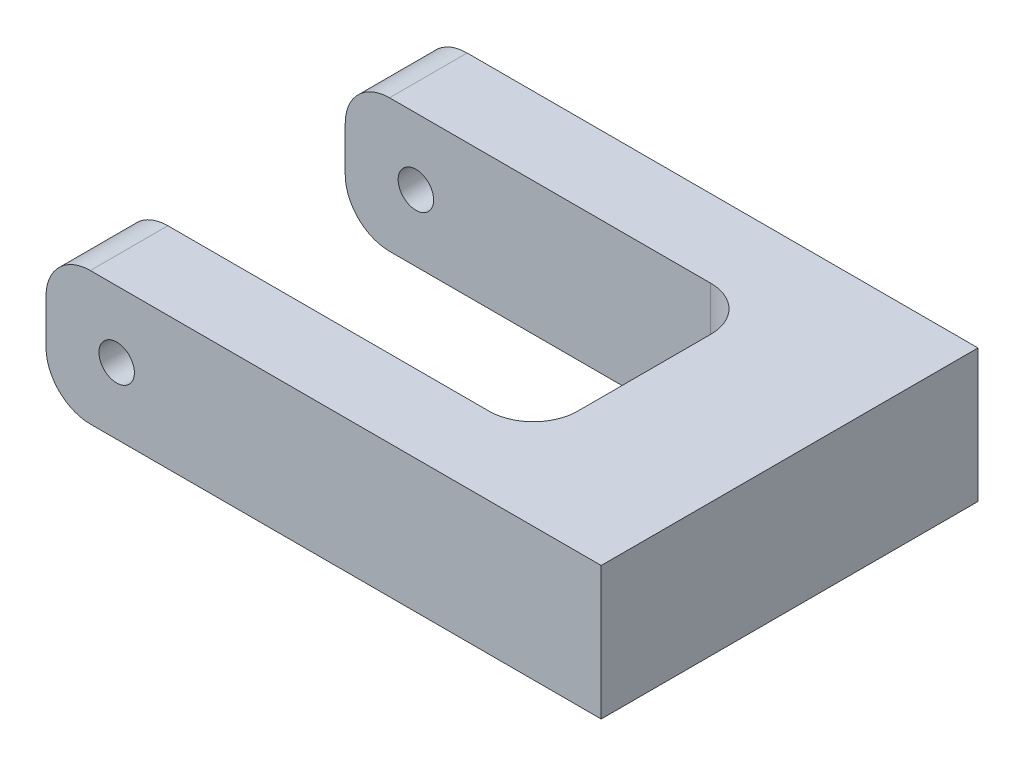
SolidWorks part; units mm, degrees
ref_plane "Спереди" through (0, 0, 0) normal (0, 0, 1) x (1, 0, 0)
ref_plane "Сверху" through (0, 0, 0) normal (0, 1, 0) x (1, 0, 0)
ref_plane "Справа" through (0, 0, 0) normal (1, 0, 0) x (0, 0, -1)
sketch "Эскиз1" plane through (0, 0, 0) normal (0, 0, 1) x (1, 0, 0)
  line L0 (-0.1149, -4.0419) -> (-0.1149, -14.0419)
  line L3 (9.8851, -24.0419) -> (125.1317, -24.0419)
  line L4 (9.8851, 5.9581) -> (125.1317, 5.9581)
  line L5 (125.1317, 5.9581) -> (125.1317, -24.0419)
  line L6 (15.824, -9.0419) -> (68.2142, -9.0419) construction
  arc A0 (-0.1149, -4.0419) -> (9.8851, 5.9581) centre (9.8851, -4.0419) cw
  arc A1 (-0.1149, -14.0419) -> (9.8851, -24.0419) centre (9.8851, -14.0419) ccw
  dimension "D1" = 10
  dimension "D2" = 15
extrude "Вытянуть1" add sketch "Эскиз1" against normal blind 85 from offset 7.5
sketch "Эскиз3" plane through (0, 0, 0) normal (0, 1, 0) x (1, 0, 0)
  line L0 (-2.2661, 60) -> (92.3282, 60)
  line L1 (92.3282, 60) -> (92.3282, 10)
  line L2 (92.3282, 10) -> (-2.2661, 10)
  line L4 (-2.2661, 10) -> (-2.2661, 60)
  line L8 (125.1317, 77.5) -> (9.8851, 77.5) construction
  line L9 (125.1317, -7.5) -> (9.8851, -7.5) construction
  dimension "D2" = 17.5
  dimension "D3" = 17.5
extrude "Вырез-Вытянуть1" cut sketch "Эскиз3" against normal mid plane 87
sketch "Эскиз4" plane through (0, 0, 0) normal (0, 0, 1) x (1, 0, 0)
  circle A0 centre (15.824, -9.0419) radius 4
  dimension "D1" = 8
extrude "Вырез-Вытянуть2" cut sketch "Эскиз4" against normal mid plane 200
fillet "Скругление1" radius 10 2 edges at (92.3282, -9.0419, -10) (92.3282, -9.0419, -60)
